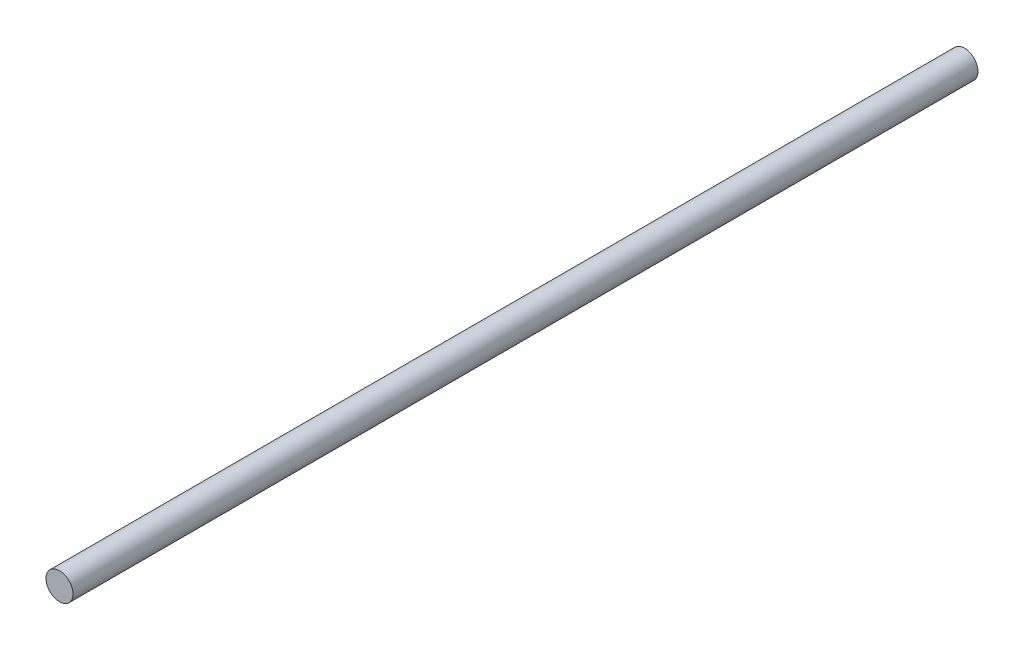
SolidWorks part; units mm, degrees
ref_plane "Plan de face" through (0, 0, 0) normal (0, 0, 1) x (1, 0, 0)
ref_plane "Plan de dessus" through (0, 0, 0) normal (0, 1, 0) x (1, 0, 0)
ref_plane "Plan de droite" through (0, 0, 0) normal (1, 0, 0) x (0, 0, -1)
sketch "Esquisse1" plane through (0, 0, 0) normal (0, 0, 1) x (1, 0, 0)
  circle A0 centre (0, 0) radius 5
  dimension "D1" = 10
extrude "Boss.-Extru.1" add sketch "Esquisse1" along normal blind 335
